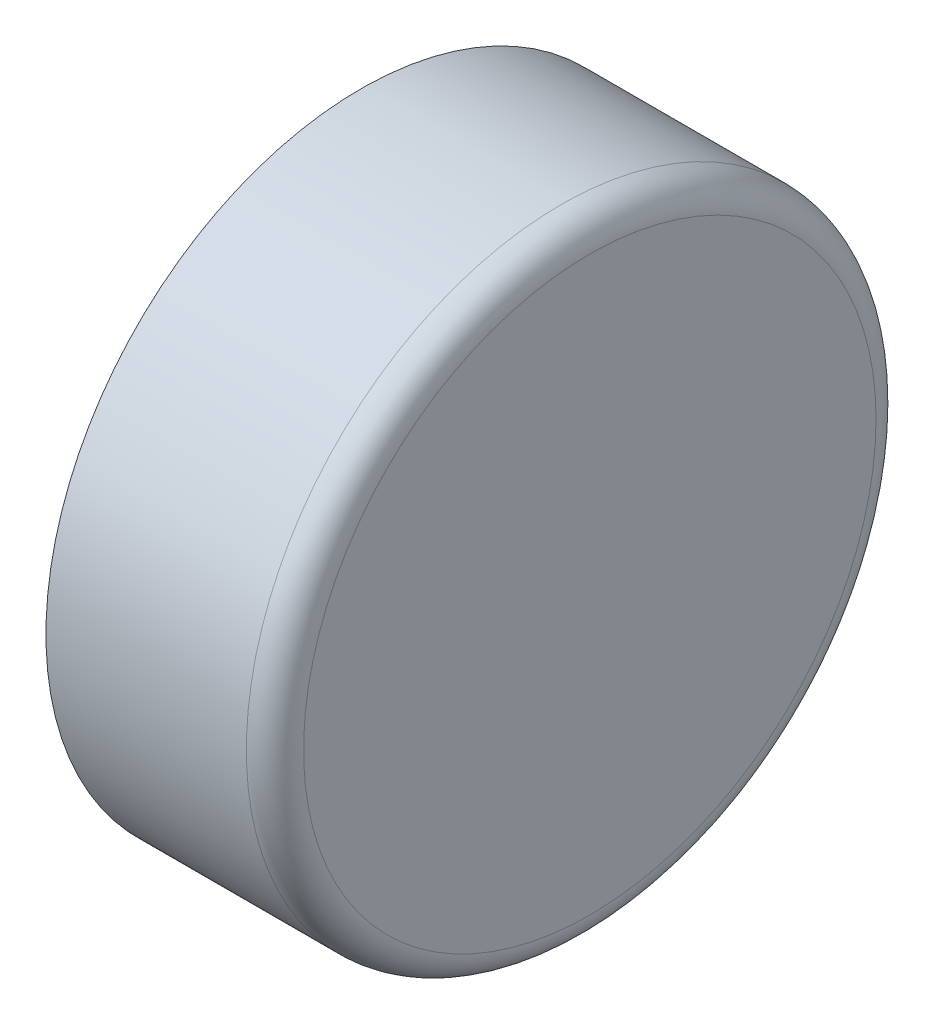
SolidWorks part; units mm, degrees
ref_plane "Front Plane" through (0, 0, 0) normal (0, 0, 1) x (1, 0, 0)
ref_plane "Top Plane" through (0, 0, 0) normal (0, 1, 0) x (1, 0, 0)
ref_plane "Right Plane" through (0, 0, 0) normal (1, 0, 0) x (0, 0, -1)
sketch "Sketch1" plane through (0, 0, 0) normal (1, 0, 0) x (0, 0, -1)
  circle A0 centre (0, 0) radius 11
  dimension "D1" = 22
extrude "Boss-Extrude1" add sketch "Sketch1" along normal blind 8
sketch "Sketch2" plane through (0, 0, 0) normal (-1, 0, 0) x (0, 0, 1)
  circle A0 centre (0, 0) radius 3
  dimension "D1" = 6
extrude "Cut-Extrude1" cut sketch "Sketch2" against normal offset from surface (7 mm away) 1 up to face at (8, 0, -11)
fillet "Fillet1" radius 1 1 edges at (8, 0, -11)
